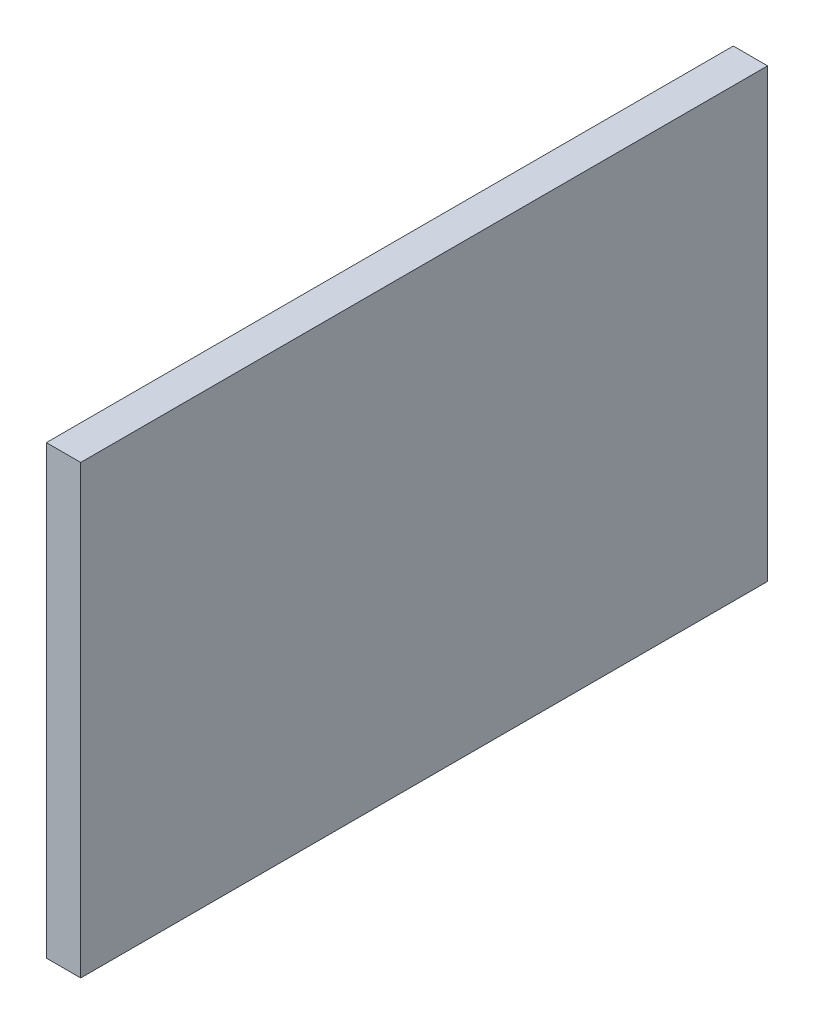
SolidWorks part; units mm, degrees
material "Alloy Steel (SS)"
ref_plane "Front Plane" through (0, 0, 0) normal (0, 0, 1) x (1, 0, 0)
ref_plane "Top Plane" through (0, 0, 0) normal (0, 1, 0) x (1, 0, 0)
ref_plane "Right Plane" through (0, 0, 0) normal (1, 0, 0) x (0, 0, -1)
sketch "Sketch1" plane through (0, 0, 0) normal (1, 0, 0) x (0, 0, -1)
  line L1 (-466.8184, 26.8007) -> (41.1816, 26.8007)
  line L2 (-466.8184, 26.8007) -> (-466.8184, -303.3993)
  line L3 (-466.8184, -303.3993) -> (41.1816, -303.3993)
  line L4 (41.1816, 26.8007) -> (41.1816, -303.3993)
  dimension "D1" = 508
  dimension "D2" = 330.2
extrude "Boss-Extrude1" add sketch "Sketch1" along normal blind 25.4
sketch "Sketch3" plane through (0, 0, 0) normal (-1, 0, 0) x (0, 0, 1)
  line L0 (-41.1816, 26.8007) -> (466.8184, 26.8007) construction
  line L1 (-41.1816, -303.3993) -> (-41.1816, 26.8007) construction
  circle A0 centre (9.6184, -23.9993) radius 12.7
  dimension "D1" = 25.4
  dimension "D2" = 50.8
  dimension "D3" = 50.8
extrude "Cut-Extrude2" cut sketch "Sketch3" against normal blind 6.35
